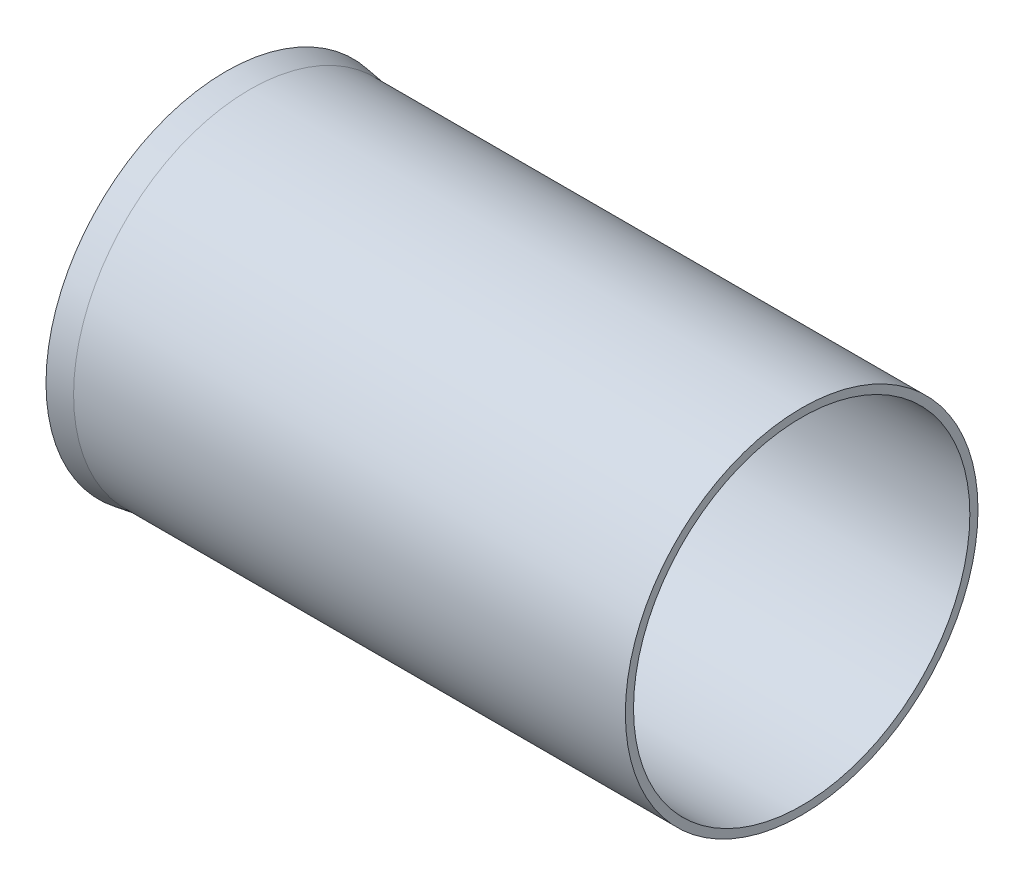
SolidWorks part; units mm, degrees
ref_plane "Plano frontal" through (0, 0, 0) normal (0, 0, 1) x (1, 0, 0)
ref_plane "Plano superior" through (0, 0, 0) normal (0, 1, 0) x (1, 0, 0)
ref_plane "Plano direito" through (0, 0, 0) normal (1, 0, 0) x (0, 0, -1)
sketch "Esboço2" plane through (0, 0, 0) normal (0, 0, 1) x (1, 0, 0)
  line L0 (0, 3.75) -> (0.5, 3.675)
  line L1 (0.5, 3.675) -> (12, 3.675)
  line L2 (-0.0252, 3.5819) -> (0.4873, 3.505)
  line L3 (0.4873, 3.505) -> (12, 3.505)
  line L4 (-0.0252, 3.5819) -> (0, 3.75)
  line L5 (12, 3.675) -> (12, 3.505)
  line L6 (0, 0) -> (12, 0) construction
  dimension "D1" = 12
  dimension "D2" = 0.5
  dimension "D3" = 3.75
  dimension "D4" = 3.675
  dimension "D5" = 0.17
revolve "Revolução1" add sketch "Esboço2" angle 360 about L6
